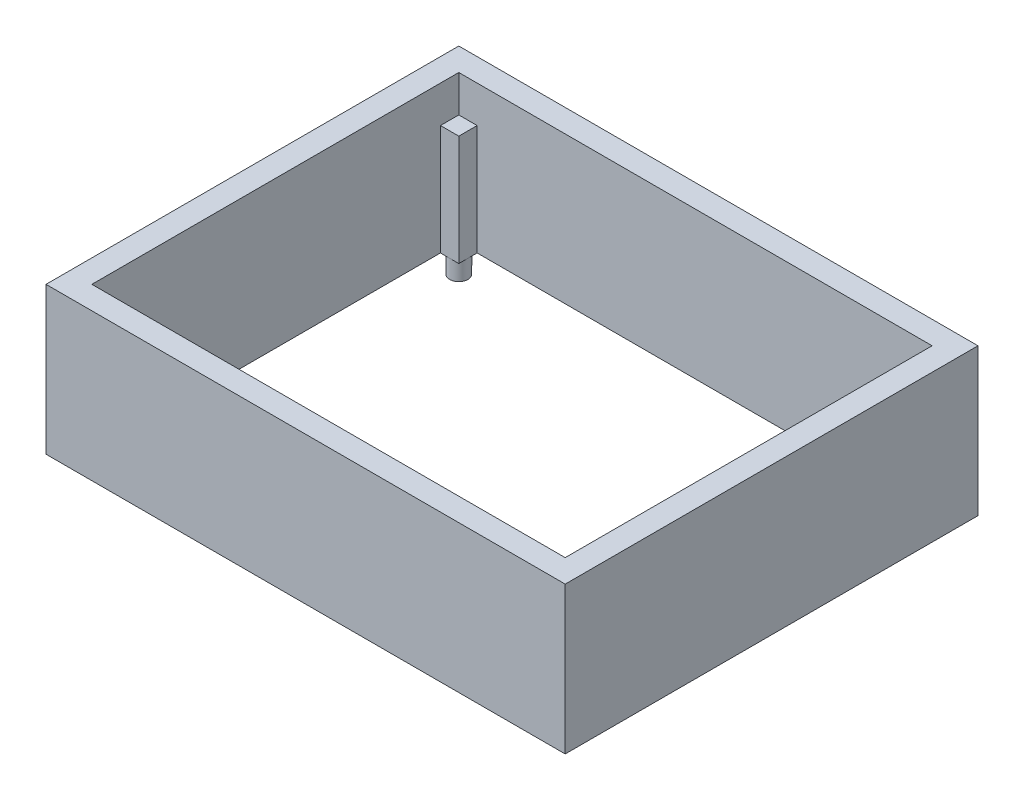
SolidWorks part; units mm, degrees
ref_plane "Front Plane" through (0, 0, 0) normal (0, 0, 1) x (1, 0, 0)
ref_plane "Top Plane" through (0, 0, 0) normal (0, 1, 0) x (1, 0, 0)
ref_plane "Right Plane" through (0, 0, 0) normal (1, 0, 0) x (0, 0, -1)
sketch "Sketch1" plane through (0, 0, 0) normal (0, 1, 0) x (1, 0, 0)
  line L1 (0, 0) -> (283, 0)
  line L2 (0, 0) -> (0, 225)
  line L3 (0, 225) -> (283, 225)
  line L4 (283, 0) -> (283, 225)
  dimension "D1" = 225
  dimension "D2" = 283
extrude "Boss-Extrude1" add sketch "Sketch1" along normal blind 80.2 contours L1 L4 L3 L2
sketch "Sketch2" plane through (0, 80.2, 0) normal (0, 1, 0) x (1, 0, 0)
  line L14 (12.5, 12.5) -> (270.5, 12.5)
  line L15 (270.5, 12.5) -> (270.5, 212.5)
  line L16 (270.5, 212.5) -> (12.5, 212.5)
  line L17 (12.5, 212.5) -> (12.5, 12.5)
  line L18 (12.5, 12.5) -> (270.5, 12.5)
  line L19 (270.5, 12.5) -> (270.5, 212.5)
  line L20 (270.5, 212.5) -> (12.5, 212.5)
  line L21 (12.5, 212.5) -> (12.5, 12.5)
  dimension "D1" = 12.5
extrude "Cut-Extrude1" cut sketch "Sketch2" against normal up to surface (80.2 mm away) contours L21 L18 L19 L20 up to face at (141.5, 0, -112.5)
sketch "Sketch3" plane through (0, 0, 0) normal (0, -1, 0) x (1, 0, 0)
  line L1 (12.5, -12.5) -> (22.5, -12.5)
  line L2 (12.5, -12.5) -> (12.5, -22.5)
  line L3 (12.5, -22.5) -> (22.5, -22.5)
  line L4 (22.5, -12.5) -> (22.5, -22.5)
  line L5 (12.5, -212.5) -> (22.5, -212.5)
  line L6 (12.5, -212.5) -> (12.5, -202.5)
  line L7 (12.5, -202.5) -> (22.5, -202.5)
  line L8 (22.5, -212.5) -> (22.5, -202.5)
  line L9 (270.5, -212.5) -> (260.5, -212.5)
  line L10 (270.5, -212.5) -> (270.5, -202.5)
  line L11 (270.5, -202.5) -> (260.5, -202.5)
  line L12 (260.5, -212.5) -> (260.5, -202.5)
  line L13 (270.5, -12.5) -> (260.5, -12.5)
  line L14 (270.5, -12.5) -> (270.5, -22.5)
  line L15 (270.5, -22.5) -> (260.5, -22.5)
  line L16 (260.5, -12.5) -> (260.5, -22.5)
  dimension "D1" = 10
  dimension "D2" = 10
  dimension "D3" = 10
  dimension "D4" = 10
  dimension "D5" = 10
  dimension "D6" = 10
  dimension "D7" = 10
  dimension "D8" = 10
extrude "Boss-Extrude2" add sketch "Sketch3" against normal blind 60.16
sketch "Sketch4" plane through (0, 0, 0) normal (0, -1, 0) x (1, 0, 0)
  line L0 (17.5, -202.5) -> (17.5, -207.5) construction
  line L1 (22.5, -202.5) -> (12.5, -202.5) construction
  line L2 (17.5, -207.5) -> (22.5, -207.5) construction
  line L3 (22.5, -212.5) -> (22.5, -202.5) construction
  line L4 (17.5, -22.5) -> (17.5, -17.5) construction
  line L5 (12.5, -22.5) -> (22.5, -22.5) construction
  line L6 (17.5, -17.5) -> (22.5, -17.5) construction
  line L7 (22.5, -22.5) -> (22.5, -12.5) construction
  line L8 (260.5, -207.5) -> (265.5, -207.5) construction
  line L9 (260.5, -202.5) -> (260.5, -212.5) construction
  line L10 (265.5, -207.5) -> (265.5, -202.5) construction
  line L11 (270.5, -202.5) -> (260.5, -202.5) construction
  line L12 (260.5, -22.5) -> (270.5, -22.5) construction
  line L13 (265.5, -22.5) -> (265.5, -17.5) construction
  line L14 (265.5, -17.5) -> (260.5, -17.5) construction
  line L15 (260.5, -12.5) -> (260.5, -22.5) construction
  circle A0 centre (17.5, -17.5) radius 5
  circle A1 centre (265.5, -17.5) radius 5
  circle A2 centre (265.5, -207.5) radius 5
  circle A3 centre (17.5, -207.5) radius 5
  dimension "D1" = 10
  dimension "D2" = 10
  dimension "D3" = 10
  dimension "D4" = 10
extrude "Boss-Extrude3" add sketch "Sketch4" along normal blind 10
equation "\"Length\" = 283mm"
equation "\"Width\" = 225mm"
equation "\"WallThickness\" = 12.5mm"
equation "\"UpperWaterJacketThickness\" = 28mm"
equation "\"D1@Sketch1\"=\"Width\""
equation "\"D2@Sketch1\"=\"Length\""
equation "\"SpacerHeight\" = 80.2mm"
equation "\"D1@Boss-Extrude1\"=\"SpacerHeight\""
equation "\"D1@Sketch2\"=\"WallThickness\""
equation "\"SpacerCornerWidth\"=10"
equation "\"D1@Sketch3\"=\"SpacerCornerWidth\""
equation "\"D2@Sketch3\"=\"SpacerCornerWidth\""
equation "\"D3@Sketch3\"=\"SpacerCornerWidth\""
equation "\"D4@Sketch3\"=\"SpacerCornerWidth\""
equation "\"D5@Sketch3\"=\"SpacerCornerWidth\""
equation "\"D6@Sketch3\"=\"SpacerCornerWidth\""
equation "\"D7@Sketch3\"=\"SpacerCornerWidth\""
equation "\"D8@Sketch3\"=\"SpacerCornerWidth\""
equation "\"SpacerCornerHeight\"=60.16"
equation "\"D1@Boss-Extrude2\"=\"SpacerCornerHeight\""
equation "\"SpacerPegDiameter\"=10"
equation "\"D1@Sketch4\"=\"SpacerPegDiameter\""
equation "\"D2@Sketch4\"=\"SpacerPegDiameter\""
equation "\"D3@Sketch4\"=\"SpacerPegDiameter\""
equation "\"D4@Sketch4\"=\"SpacerPegDiameter\""
equation "\"SpacerPegHeight\"=10"
equation "\"D1@Boss-Extrude3\"=\"SpacerPegHeight\""
